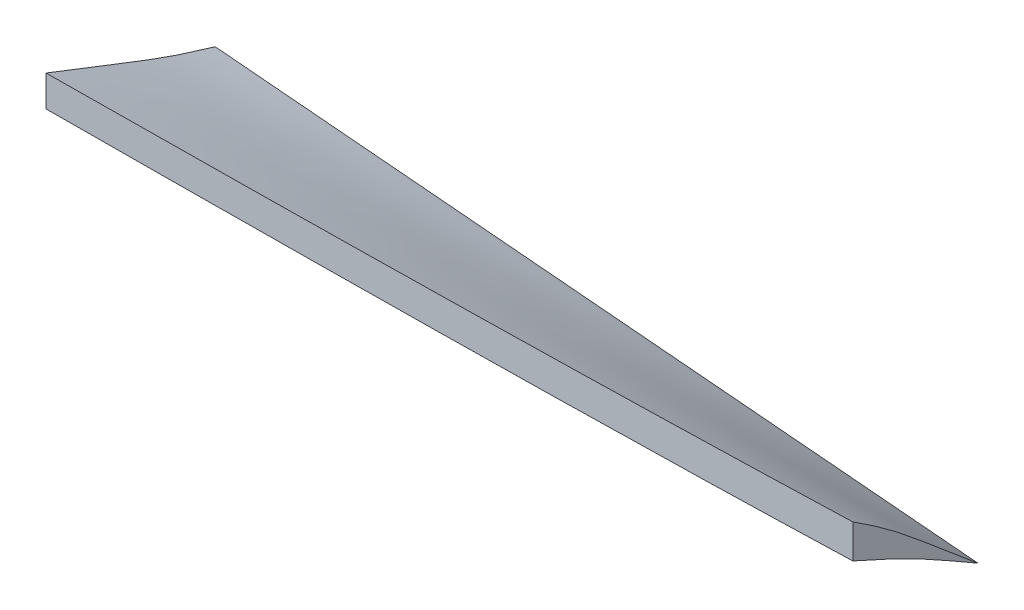
SolidWorks part; units mm, degrees
material "Balsa"
ref_plane "Front Plane" through (0, 0, 0) normal (0, 0, 1) x (1, 0, 0)
ref_plane "Top Plane" through (0, 0, 0) normal (0, 1, 0) x (1, 0, 0)
ref_plane "Right Plane" through (0, 0, 0) normal (1, 0, 0) x (0, 0, -1)
ref_plane "Plane1" through (266.7, 0, 0) normal (1, 0, 0) x (0, 0, -1)
ref_plane "Plane2" through (374.396, 0, 0) normal (1, 0, 0) x (0, 0, -1)
sketch "Sketch1" plane through (266.7, 0, 0) normal (1, 0, 0) x (0, 0, -1)
  spline S0 degree 3 poles (-1994.7901, -130.8385) (49.5083, 45.0487) (-3.9103, 18.1854) (0.5702, -4.3968) (2.5361, -10.6164) (7.9982, -20.5501) (16.1137, -34.185) (25.7513, -48.9002) (36.932, -62.9388) (49.3364, -75.9186) (65.2269, -85.625) (84.4528, -91.7174) (106.8521, -96.1515) (132.5109, -98.5722) (161.1944, -99.0924) (192.7613, -97.7042) (227.0382, -94.5118) (263.8348, -89.6638) (302.9215, -83.3884) (344.0178, -75.9778) (386.7768, -67.7807) (430.7746, -59.2023) (475.4963, -50.6638) (520.3353, -42.6036) (564.5889, -35.4228) (607.4709, -29.4733) (648.1275, -25.0145) (685.6676, -22.1862) (719.1968, -21.0048) (747.8303, -21.2786) (770.6884, -22.8547) (787.0914, -25.0735) (855.7552, -37.3672) (910.4178, -89.1553) (1388.6423, 1880.9845) knots -0.071347 -0.071347 -0.071347 -0.071347 0.001821 0.004613 0.009135 0.024676 0.044153 0.064937 0.086321 0.107138 0.1276 0.150893 0.177565 0.207668 0.241222 0.278203 0.318526 0.362031 0.408465 0.457479 0.508614 0.561296 0.614835 0.668438 0.721214 0.772202 0.820393 0.864766 0.904324 0.938132 0.965242 0.98469 0.99621 1.210002 1.210002 1.210002 1.210002 only from (0, 0) to (802.1511, -28.0117) construction
  spline S1 degree 3 poles (304.4894, -1963.048) (904.56, -11.0089) (840.5576, -43.532) (789.3572, -23.4586) (777.0615, -18.6436) (760.5817, -13.0401) (739.9968, -7.1233) (715.5772, -0.3798) (687.647, 7.013) (656.6835, 14.9584) (623.1589, 23.2583) (587.5492, 31.6944) (550.3192, 40.0262) (511.9148, 48.0016) (472.7617, 55.3745) (433.2622, 61.9128) (393.7959, 67.4048) (354.7199, 71.6552) (316.357, 74.5357) (278.9313, 75.7536) (242.6994, 75.3938) (207.8706, 73.5467) (174.7468, 70.259) (143.6014, 65.7682) (114.7621, 60.1875) (88.5345, 53.6285) (65.199, 46.2382) (45.0006, 38.1339) (28.1586, 29.5092) (14.871, 20.5578) (6.1442, 12.3133) (1.9481, 6.1765) (0.6391, 3.0841) (0.217, 1.668) (-2.2377, -10.856) (31.8726, -26.5577) (-1993.0578, 155.2139) knots -0.166991 -0.166991 -0.166991 -0.166991 0.003802 0.014472 0.030564 0.051299 0.077028 0.107574 0.142399 0.180921 0.222525 0.266591 0.312515 0.35971 0.407632 0.455773 0.503669 0.550901 0.597096 0.641976 0.685512 0.727353 0.767354 0.805169 0.840471 0.872937 0.902335 0.928425 0.951113 0.970253 0.985871 0.993982 0.996753 0.997907 0.999293 1.04244 1.04244 1.04244 1.04244 only from (802.1511, -28.0117) to (0, 0) construction
  spline S2 degree 3 poles (0, 0) (0.0175, -0.519) (0.0617, -1.8338) (0.5702, -4.3968) (2.5361, -10.6164) (7.9982, -20.5501) (16.1137, -34.185) (25.7513, -48.9002) (36.932, -62.9388) (49.3364, -75.9186) (65.2269, -85.625) (84.4528, -91.7174) (106.8521, -96.1515) (132.5109, -98.5722) (161.1944, -99.0924) (192.7613, -97.7042) (227.0382, -94.5118) (263.8348, -89.6638) (302.9215, -83.3884) (344.0178, -75.9778) (386.7768, -67.7807) (430.7746, -59.2023) (475.4963, -50.6638) (520.3353, -42.6036) (564.5889, -35.4228) (607.4709, -29.4733) (648.1275, -25.0145) (685.6676, -22.1862) (719.1968, -21.0048) (747.8303, -21.2786) (770.6884, -22.8547) (787.0914, -25.0735) (796.8423, -26.8193) (801.0977, -27.7751) (802.1511, -28.0117) knots 0 0 0 0 0.001821 0.004613 0.009135 0.024676 0.044153 0.064937 0.086321 0.107138 0.1276 0.150893 0.177565 0.207668 0.241222 0.278203 0.318526 0.362031 0.408465 0.457479 0.508614 0.561296 0.614835 0.668438 0.721214 0.772202 0.820393 0.864766 0.904324 0.938132 0.965242 0.98469 0.99621 1 1 1 1
  spline S3 degree 3 poles (802.1511, -28.0117) (801.1372, -27.7105) (797.2784, -26.5642) (789.3572, -23.4586) (777.0615, -18.6436) (760.5817, -13.0401) (739.9968, -7.1233) (715.5772, -0.3798) (687.647, 7.013) (656.6835, 14.9584) (623.1589, 23.2583) (587.5492, 31.6944) (550.3192, 40.0262) (511.9148, 48.0016) (472.7617, 55.3745) (433.2622, 61.9128) (393.7959, 67.4048) (354.7199, 71.6552) (316.357, 74.5357) (278.9313, 75.7536) (242.6994, 75.3938) (207.8706, 73.5467) (174.7468, 70.259) (143.6014, 65.7682) (114.7621, 60.1875) (88.5345, 53.6285) (65.199, 46.2382) (45.0006, 38.1339) (28.1586, 29.5092) (14.871, 20.5578) (6.1442, 12.3133) (1.9481, 6.1765) (0.6391, 3.0841) (0.217, 1.668) (0.0426, 0.7778) (0.0107, 0.1963) (0, 0) knots 0 0 0 0 0.003802 0.014472 0.030564 0.051299 0.077028 0.107574 0.142399 0.180921 0.222525 0.266591 0.312515 0.35971 0.407632 0.455773 0.503669 0.550901 0.597096 0.641976 0.685512 0.727353 0.767354 0.805169 0.840471 0.872937 0.902335 0.928425 0.951113 0.970253 0.985871 0.993982 0.996753 0.997907 0.999293 1 1 1 1
sketch "Sketch2" plane through (374.396, 0, 0) normal (1, 0, 0) x (0, 0, -1)
  spline S0 degree 3 poles (-2757.0722, -63.1376) (319.972, 43.9085) (236.8558, 18.6742) (241.6902, -3.5548) (242.7876, -5.2858) (244.5591, -6.4782) (246.6935, -7.2344) (249.131, -7.7493) (251.9053, -8.1096) (255.0978, -8.3654) (258.8342, -8.5393) (263.2977, -8.6228) (268.7514, -8.5985) (275.555, -8.4304) (284.1155, -8.069) (294.702, -7.4673) (307.2387, -6.5655) (321.3512, -5.2677) (336.6352, -3.4986) (352.8428, -1.3174) (369.8087, 1.1216) (387.3069, 3.7048) (405.0531, 6.3509) (422.7994, 8.9824) (440.3769, 11.53) (457.7079, 13.943) (474.7726, 16.1729) (491.5765, 18.1853) (508.1369, 19.9445) (524.4805, 21.4229) (540.634, 22.6007) (556.6259, 23.457) (572.4794, 23.9812) (588.218, 24.1589) (603.8592, 23.9828) (619.4184, 23.4456) (634.8979, 22.5455) (650.289, 21.2804) (665.5566, 19.6555) (680.6274, 17.677) (695.3633, 15.3749) (709.5387, 12.7829) (722.8509, 9.9708) (734.984, 7.0126) (745.7106, 3.9665) (754.9656, 0.8711) (762.813, -2.2676) (837.931, -37.2134) (855.9752, -173.8618) (2373.6724, 2523.7984) knots -0.112962 -0.112962 -0.112962 -0.112962 0.002957 0.006514 0.010125 0.013912 0.018 0.022509 0.02757 0.033355 0.040094 0.048109 0.05787 0.070043 0.085482 0.104923 0.128275 0.154506 0.182747 0.212766 0.244316 0.276878 0.309905 0.342853 0.375404 0.407446 0.438949 0.469916 0.500388 0.530405 0.560035 0.58933 0.61835 0.647141 0.675763 0.704248 0.732633 0.760909 0.78905 0.816946 0.844378 0.870951 0.896076 0.91909 0.939522 0.957298 0.972656 0.985921 1.411798 1.411798 1.411798 1.411798 only from (241.3, 0) to (776.3965, -9.3401) construction
  spline S1 degree 3 poles (-913.9077, -2480.4045) (935.2001, -71.4809) (834.1009, -60.2269) (768.0238, -2.1794) (762.2183, 1.8486) (755.2432, 5.6003) (746.9128, 9.3355) (737.0183, 13.2386) (725.4787, 17.3162) (712.4284, 21.5116) (698.1677, 25.7421) (683.0626, 29.924) (667.4447, 33.9819) (651.5631, 37.8588) (635.5717, 41.5076) (619.5421, 44.8962) (603.4804, 48.0063) (587.348, 50.8385) (571.0793, 53.4037) (554.5973, 55.7298) (537.8317, 57.8519) (520.7417, 59.8204) (503.3402, 61.6856) (485.7107, 63.4899) (468.0112, 65.2499) (450.4595, 66.9518) (433.3115, 68.5379) (416.8415, 69.9289) (401.2965, 71.0328) (386.8087, 71.7296) (373.3513, 71.8938) (360.7833, 71.4603) (348.942, 70.4185) (337.7011, 68.7634) (326.9806, 66.4985) (316.7399, 63.6365) (306.9731, 60.2063) (297.7138, 56.2454) (289.0297, 51.8366) (281.0253, 47.1113) (273.817, 42.2564) (267.5024, 37.4676) (262.1111, 32.912) (257.6099, 28.6711) (253.9113, 24.7595) (250.9022, 21.1572) (248.4636, 17.8395) (246.4919, 14.7802) (244.9074, 11.9506) (243.6495, 9.3232) (242.6798, 6.8706) (241.9668, 4.5716) (241.4951, 2.4096) (239.7085, -13.416) (262.9843, -29.3789) (-2756.235, 61.0933) knots -0.427147 -0.427147 -0.427147 -0.427147 0.007664 0.018831 0.030906 0.044389 0.060047 0.078461 0.099805 0.123817 0.149891 0.177318 0.205492 0.23398 0.26251 0.290968 0.319358 0.347763 0.376321 0.405183 0.434504 0.464387 0.494832 0.525708 0.55674 0.587526 0.617605 0.646485 0.67366 0.698816 0.722063 0.743776 0.764323 0.783978 0.802952 0.821386 0.839352 0.856859 0.873831 0.890071 0.905268 0.919096 0.931351 0.942034 0.951308 0.959388 0.966479 0.972752 0.978344 0.983369 0.987921 0.992076 0.995899 0.999439 1.074824 1.074824 1.074824 1.074824 only from (776.3965, -9.3401) to (241.3, 0) construction
  spline S2 degree 3 poles (241.3, 0) (241.2977, -0.539) (241.2925, -1.7262) (241.6902, -3.5548) (242.7876, -5.2858) (244.5591, -6.4782) (246.6935, -7.2344) (249.131, -7.7493) (251.9053, -8.1096) (255.0978, -8.3654) (258.8342, -8.5393) (263.2977, -8.6228) (268.7514, -8.5985) (275.555, -8.4304) (284.1155, -8.069) (294.702, -7.4673) (307.2387, -6.5655) (321.3512, -5.2677) (336.6352, -3.4986) (352.8428, -1.3174) (369.8087, 1.1216) (387.3069, 3.7048) (405.0531, 6.3509) (422.7994, 8.9824) (440.3769, 11.53) (457.7079, 13.943) (474.7726, 16.1729) (491.5765, 18.1853) (508.1369, 19.9445) (524.4805, 21.4229) (540.634, 22.6007) (556.6259, 23.457) (572.4794, 23.9812) (588.218, 24.1589) (603.8592, 23.9828) (619.4184, 23.4456) (634.8979, 22.5455) (650.289, 21.2804) (665.5566, 19.6555) (680.6274, 17.677) (695.3633, 15.3749) (709.5387, 12.7829) (722.8509, 9.9708) (734.984, 7.0126) (745.7106, 3.9665) (754.9656, 0.8711) (762.813, -2.2676) (769.8706, -5.5509) (774.1784, -8.0522) (776.3965, -9.3401) knots 0 0 0 0 0.002957 0.006514 0.010125 0.013912 0.018 0.022509 0.02757 0.033355 0.040094 0.048109 0.05787 0.070043 0.085482 0.104923 0.128275 0.154506 0.182747 0.212766 0.244316 0.276878 0.309905 0.342853 0.375404 0.407446 0.438949 0.469916 0.500388 0.530405 0.560035 0.58933 0.61835 0.647141 0.675763 0.704248 0.732633 0.760909 0.78905 0.816946 0.844378 0.870951 0.896076 0.91909 0.939522 0.957298 0.972656 0.985921 1 1 1 1
  spline S3 degree 3 poles (776.3965, -9.3401) (775.2642, -8.4018) (772.4822, -6.0961) (768.0238, -2.1794) (762.2183, 1.8486) (755.2432, 5.6003) (746.9128, 9.3355) (737.0183, 13.2386) (725.4787, 17.3162) (712.4284, 21.5116) (698.1677, 25.7421) (683.0626, 29.924) (667.4447, 33.9819) (651.5631, 37.8588) (635.5717, 41.5076) (619.5421, 44.8962) (603.4804, 48.0063) (587.348, 50.8385) (571.0793, 53.4037) (554.5973, 55.7298) (537.8317, 57.8519) (520.7417, 59.8204) (503.3402, 61.6856) (485.7107, 63.4899) (468.0112, 65.2499) (450.4595, 66.9518) (433.3115, 68.5379) (416.8415, 69.9289) (401.2965, 71.0328) (386.8087, 71.7296) (373.3513, 71.8938) (360.7833, 71.4603) (348.942, 70.4185) (337.7011, 68.7634) (326.9806, 66.4985) (316.7399, 63.6365) (306.9731, 60.2063) (297.7138, 56.2454) (289.0297, 51.8366) (281.0253, 47.1113) (273.817, 42.2564) (267.5024, 37.4676) (262.1111, 32.912) (257.6099, 28.6711) (253.9113, 24.7595) (250.9022, 21.1572) (248.4636, 17.8395) (246.4919, 14.7802) (244.9074, 11.9506) (243.6495, 9.3232) (242.6798, 6.8706) (241.9668, 4.5716) (241.4951, 2.4096) (241.324, 0.8942) (241.3029, 0.1075) (241.3, 0) knots 0 0 0 0 0.007664 0.018831 0.030906 0.044389 0.060047 0.078461 0.099805 0.123817 0.149891 0.177318 0.205492 0.23398 0.26251 0.290968 0.319358 0.347763 0.376321 0.405183 0.434504 0.464387 0.494832 0.525708 0.55674 0.587526 0.617605 0.646485 0.67366 0.698816 0.722063 0.743776 0.764323 0.783978 0.802952 0.821386 0.839352 0.856859 0.873831 0.890071 0.905268 0.919096 0.931351 0.942034 0.951308 0.959388 0.966479 0.972752 0.978344 0.983369 0.987921 0.992076 0.995899 0.999439 1 1 1 1
loft "Loft1" add profiles "Sketch1", "Sketch2"
sketch "Sketch3" plane through (0, 0, 0) normal (0, 1, 0) x (1, 0, 0)
  line L0 (230.2362, 791.0809) -> (382.1753, 761.4292)
  line L1 (374.396, 762.9473) -> (266.7, 783.9648) construction
  line L5 (230.2362, 791.0809) -> (230.2362, -132.4008)
  line L6 (230.2362, -132.4008) -> (382.1753, -132.4008)
  line L7 (382.1753, -132.4008) -> (382.1753, 761.4292)
extrude "Cut-Extrude1" cut sketch "Sketch3" against normal through all both and the other way through all
